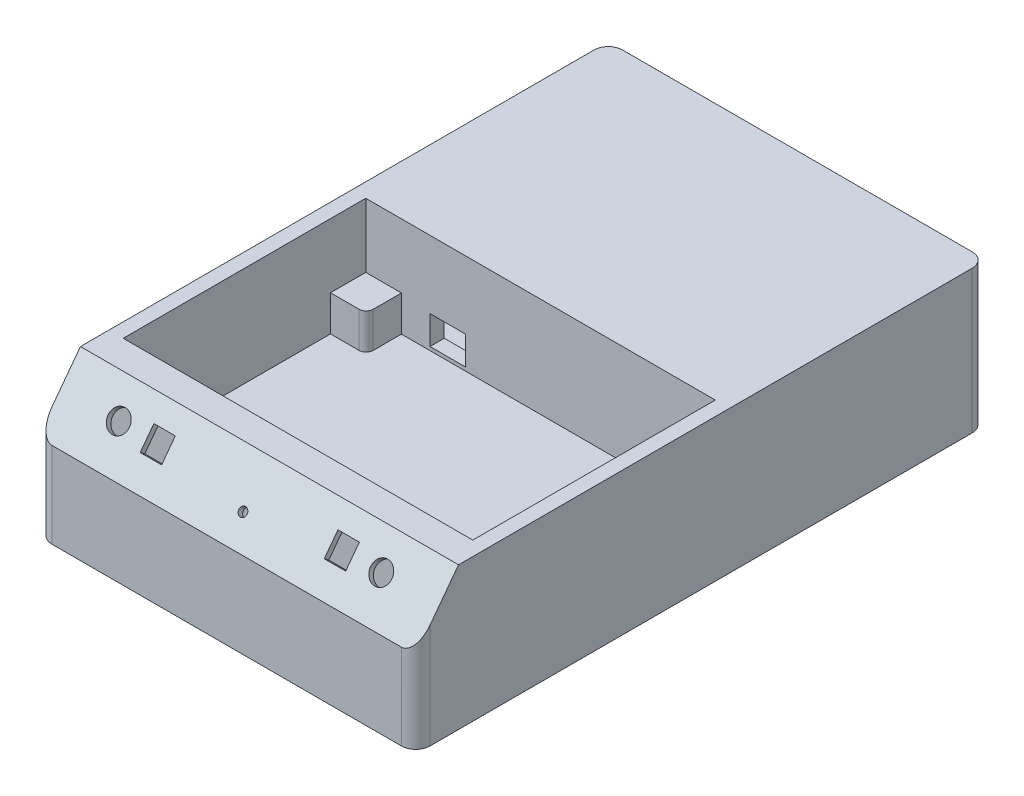
SolidWorks part; units mm, degrees
ref_plane "Front Plane" through (0, 0, 0) normal (0, 0, 1) x (1, 0, 0)
ref_plane "Top Plane" through (0, 0, 0) normal (0, 1, 0) x (1, 0, 0)
ref_plane "Right Plane" through (0, 0, 0) normal (1, 0, 0) x (0, 0, -1)
sketch "Sketch1" plane through (0, 0, 0) normal (0, 1, 0) x (1, 0, 0)
  line L0 (0, -10) -> (0, -390)
  line L1 (10, 0) -> (255, 0)
  line L2 (265, -10) -> (265, -390)
  line L3 (10, -400) -> (255, -400)
  arc A0 (0, -10) -> (10, 0) centre (10, -10) cw
  arc A1 (265, -10) -> (255, 0) centre (255, -10) ccw
  arc A2 (0, -390) -> (10, -400) centre (10, -390) ccw
  arc A3 (265, -390) -> (255, -400) centre (255, -390) cw
extrude "Boss-Extrude2" add sketch "Sketch1" along normal blind 100
ref_plane "Plane1" through (0, 100, 0) normal (0, 1, 0) x (1, 0, 0)
sketch "Sketch4" plane through (0, 100, 0) normal (0, 1, 0) x (1, 0, 0)
  line L0 (0, -10) -> (0, -390) construction
  line L1 (10, -180) -> (255, -180)
  line L2 (10, -180) -> (10, -350)
  line L3 (10, -350) -> (255, -350)
  line L4 (255, -180) -> (255, -350)
  line L5 (10, -400) -> (255, -400) construction
  dimension "D1" = 170
  dimension "D2" = 245
  dimension "D3" = 10
  dimension "D4" = 50
extrude "Cut-Extrude2" cut sketch "Sketch4" against normal blind 70
ref_plane "Plane2" through (132.5, 0, 0) normal (1, 0, 0) x (0, 0, -1)
ref_plane "Plane4" through (0, 0, 360) normal (0, 0, 1) x (1, 0, 0)
sketch "Sketch10" plane through (132.5, 0, 0) normal (1, 0, 0) x (0, 0, -1)
  line L0 (-400, 60) -> (-370, 100)
  line L1 (-400, 100) -> (-400, 0) construction
  line L2 (145.75, 100) -> (-145.75, 100) construction
  line L5 (-360, 55) -> (-360, -55) construction
  line L6 (-400, 60) -> (-400, 100)
  line L7 (-400, 100) -> (-370, 100)
  dimension "D1" = 60
  dimension "D2" = 10
extrude "Cut-Extrude12" cut sketch "Sketch10" against normal through all both and the other way through all
sketch "Sketch14" plane through (132.5, 0, 0) normal (1, 0, 0) x (0, 0, -1)
  line L0 (-390, 10) -> (-360, 10)
  line L1 (-390, 73.3333) -> (-390, 0) construction
  line L2 (-360, 33) -> (-360, -33) construction
  line L7 (-390, 66.6667) -> (-390, 10)
  line L8 (-390, 73.3333) -> (-370, 100) construction
  line L10 (-390, 0) -> (-10, 0) construction
  line L11 (-390, 66.6667) -> (-368, 96)
  line L12 (-368, 96) -> (-360, 96)
  line L13 (-360, 96) -> (-360, 10)
  line L14 (145.75, 100) -> (-145.75, 100) construction
  dimension "D1" = 4
  dimension "D2" = 4
  dimension "D3" = 4
  dimension "D4" = 10
extrude "Cut-Extrude13" cut sketch "Sketch14" against normal mid plane 245
sketch "Sketch15" plane through (132.5, 0, 0) normal (1, 0, 0) x (0, 0, -1)
  line L0 (-360, 33) -> (-360, -33) construction
  line L2 (-360, 9.7841) -> (-360, 20)
  line L3 (-360, 20) -> (-170, 20)
  line L6 (-170, 95) -> (-5, 95)
  line L9 (-5, 95) -> (-5, 10)
  line L10 (0, 100) -> (0, 0) construction
  line L11 (-180, 30) -> (-180, 100) construction
  line L12 (145.75, 100) -> (-145.75, 100) construction
  line L13 (-170, 20) -> (-170, 95)
  line L14 (-5, 10) -> (-360, 9.7841)
  dimension "D1" = 10
  dimension "D2" = 5
  dimension "D5" = 10
  dimension "D6" = 5
extrude "Cut-Extrude14" cut sketch "Sketch15" against normal mid plane 245
sketch "Sketch16" plane through (0, 0, 0) normal (0, 0, -1) x (-1, 0, 0)
  line L0 (-98.8918, 75.7878) -> (-33.8918, 75.7878)
  line L2 (-98.8918, 70.7878) -> (-33.8918, 70.7878)
  line L4 (-98.7106, 67.7878) -> (-33.7106, 67.7878)
  line L5 (-98.7106, 62.9523) -> (-33.7106, 62.9523)
  line L8 (-98.9762, 59.9523) -> (-33.9762, 59.9523)
  line L9 (-98.9762, 54.9523) -> (-33.9762, 54.9523)
  line L10 (-98.7337, 52.1958) -> (-33.7337, 52.1958)
  line L11 (-98.7337, 47.1958) -> (-33.7337, 47.1958)
  line L12 (-98.8646, 44.5988) -> (-33.8646, 44.5988)
  line L13 (-98.8646, 39.5988) -> (-33.8646, 39.5988)
  line L14 (-98.8646, 37.0018) -> (-33.8646, 37.0018)
  line L15 (-98.8646, 32.0018) -> (-33.8646, 32.0018)
  line L16 (-98.3407, 28.6189) -> (-33.3407, 28.6189)
  line L17 (-98.3407, 23.6189) -> (-33.3407, 23.6189)
  line L19 (-235, 20) -> (-206.5, 20)
  line L20 (-235, 20) -> (-235, 68)
  line L21 (-235, 68) -> (-206.5, 68)
  line L22 (-206.5, 20) -> (-206.5, 68)
  line L23 (-10, 20) -> (-255, 20) construction
  line L24 (-255, 100) -> (-255, 0) construction
  line L25 (-10, 10) -> (-255, 10) construction
  circle A36 centre (-99.3515, 82.3468) radius 2.5
  circle A37 centre (-32.7893, 14.2658) radius 2.5
  circle A38 centre (-33.3515, 80.2634) radius 2.5
  circle A39 centre (-98.7893, 16.3492) radius 2.5
  arc A40 (-98.8918, 75.7878) -> (-98.8918, 70.7878) centre (-98.8918, 73.2878) ccw
  arc A41 (-33.8918, 70.7878) -> (-33.8918, 75.7878) centre (-33.8918, 73.2878) ccw
  arc A42 (-98.7106, 67.7878) -> (-98.7106, 62.9523) centre (-98.7106, 65.37) ccw
  arc A43 (-33.7106, 62.9523) -> (-33.7106, 67.7878) centre (-33.7106, 65.37) ccw
  arc A46 (-98.9762, 59.9523) -> (-98.9762, 54.9523) centre (-98.9762, 57.4523) ccw
  arc A47 (-33.9762, 54.9523) -> (-33.9762, 59.9523) centre (-33.9762, 57.4523) ccw
  arc A48 (-98.7337, 52.1958) -> (-98.7337, 47.1958) centre (-98.7337, 49.6958) ccw
  arc A49 (-33.7337, 47.1958) -> (-33.7337, 52.1958) centre (-33.7337, 49.6958) ccw
  arc A50 (-98.8646, 44.5988) -> (-98.8646, 39.5988) centre (-98.8646, 42.0988) ccw
  arc A51 (-33.8646, 39.5988) -> (-33.8646, 44.5988) centre (-33.8646, 42.0988) ccw
  arc A52 (-98.8646, 37.0018) -> (-98.8646, 32.0018) centre (-98.8646, 34.5018) ccw
  arc A53 (-33.8646, 32.0018) -> (-33.8646, 37.0018) centre (-33.8646, 34.5018) ccw
  arc A54 (-98.3407, 28.6189) -> (-98.3407, 23.6189) centre (-98.3407, 26.1189) ccw
  arc A55 (-33.3407, 23.6189) -> (-33.3407, 28.6189) centre (-33.3407, 26.1189) ccw
  circle A56 centre (-241, 44.5988) radius 2.25
  circle A57 centre (-201, 44.5988) radius 2.25
  point P64 (-194.1214, 44.5988)
  point P65 (-240.8178, 44.5988)
  point P66 (-201, 44.5988)
  point P67 (0, 0)
  point P68 (0, 0)
  dimension "D1" = 5
  dimension "D2" = 5
  dimension "D3" = 5
  dimension "D4" = 5
  dimension "D9" = 65
  dimension "D21" = 4.5
  dimension "D5" = 66
  dimension "D6" = 66
  dimension "D7" = 66
  dimension "D8" = 66
  dimension "D10" = 3
  dimension "D11" = 3
  dimension "D12" = 65
  dimension "D13" = 65
  dimension "D14" = 65
  dimension "D15" = 65
  dimension "D16" = 65
  dimension "D17" = 28.5
  dimension "D18" = 48
  dimension "D19" = 20
  dimension "D20" = 10
  dimension "D22" = 40
extrude "Cut-Extrude15" cut sketch "Sketch16" against normal blind 30
sketch "Sketch17" plane through (0, 213.6, 284.8) normal (0, 0.6, 0.8) x (1, 0, 0)
  line L0 (132.5, -55) -> (132.5, 55) construction
  line L1 (60.5, -157) -> (75.5, -157)
  line L2 (60.5, -157) -> (60.5, -173)
  line L3 (60.5, -173) -> (75.5, -173)
  line L4 (75.5, -157) -> (75.5, -173)
  line L5 (189.5, -157) -> (204.5, -157)
  line L6 (189.5, -157) -> (189.5, -173)
  line L7 (189.5, -173) -> (204.5, -173)
  line L8 (204.5, -157) -> (204.5, -173)
  line L9 (0, -142) -> (265, -142) construction
  circle A0 centre (132.5, -173) radius 2.9529
  circle A1 centre (40.5, -164.7277) radius 7.5
  circle A2 centre (224.5, -164.7277) radius 7.5
  dimension "D9" = 15
  dimension "D10" = 15
  dimension "D1" = 16
  dimension "D2" = 15
  dimension "D3" = 16
  dimension "D4" = 57
  dimension "D5" = 57
  dimension "D6" = 15
  dimension "D7" = 15
  dimension "D8" = 15
  dimension "D11" = 20
  dimension "D12" = 20
extrude "Cut-Extrude16" cut sketch "Sketch17" against normal blind 10
sketch "Sketch18" plane through (0, 30, 0) normal (0, 1, 0) x (1, 0, 0)
  line L0 (10, -180) -> (10, -204.7299)
  line L1 (10, -180) -> (10, -350) construction
  line L2 (10, -204.7299) -> (30, -204.7299)
  line L3 (10, -180) -> (34.9927, -180)
  line L4 (34.9927, -180) -> (34.9927, -200)
  line L5 (255, -350) -> (255, -324.1491)
  line L6 (255, -350) -> (255, -180) construction
  line L7 (255, -324.1491) -> (235, -324.1491)
  line L8 (255, -350) -> (230.0729, -350)
  line L9 (10, -350) -> (255, -350) construction
  line L10 (230.0729, -350) -> (230.0729, -330)
  arc A0 (30, -204.7299) -> (34.9927, -200) centre (30, -199.7299) ccw
  arc A1 (235, -324.1491) -> (230.0729, -330) centre (235, -329.1491) ccw
  dimension "D1" = 5
  dimension "D2" = 20
  dimension "D3" = 20
  dimension "D4" = 5
  dimension "D5" = 20
  dimension "D6" = 20
extrude "Boss-Extrude3" add sketch "Sketch18" along normal blind 25
sketch "Sketch19" plane through (0, 0, 180) normal (0, 0, 1) x (1, 0, 0)
  line L0 (10, 55) -> (30, 55) construction
  line L3 (54.9927, 52.5) -> (79.9927, 52.5)
  line L5 (54.9927, 32.5) -> (79.9927, 32.5)
  line L6 (54.9927, 52.5) -> (54.9927, 32.5)
  line L7 (79.9927, 32.5) -> (79.9927, 52.5)
  line L8 (10, 30) -> (230.0729, 30) construction
  line L9 (34.9927, 55) -> (34.9927, 30) construction
  dimension "D1" = 2.5
  dimension "D2" = 2.5
  dimension "D3" = 25
  dimension "D4" = 20
extrude "Cut-Extrude17" cut sketch "Sketch19" against normal blind 15
sketch "Sketch21" plane through (0, 20, 0) normal (0, -1, 0) x (1, 0, 0)
  line L9 (10, 170) -> (255, 170) construction
  line L10 (34.9927, 170) -> (230.0729, 170)
  line L11 (34.9927, 170) -> (34.9927, 360)
  line L12 (34.9927, 360) -> (230.0729, 360)
  line L13 (230.0729, 170) -> (230.0729, 360)
  line L14 (33, 360) -> (-33, 360) construction
extrude "Boss-Extrude9" add sketch "Sketch21" along normal blind 10 separate body
